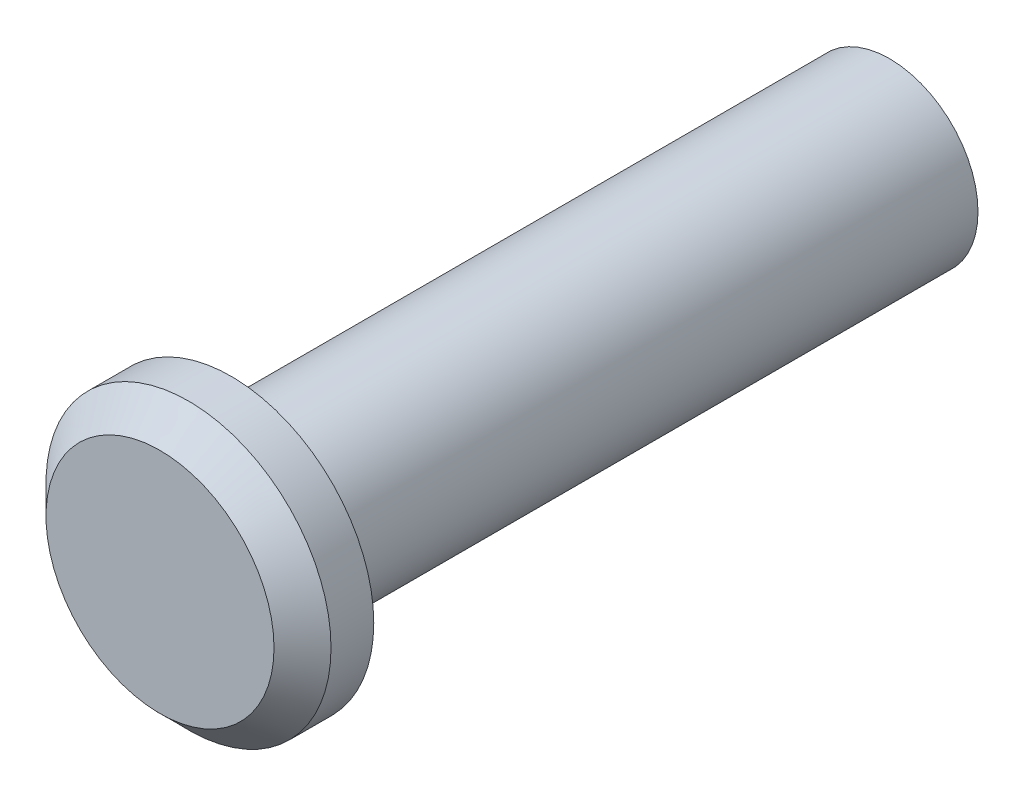
SolidWorks part; units mm, degrees
ref_plane "Front Plane" through (0, 0, 0) normal (0, 0, 1) x (1, 0, 0)
ref_plane "Top Plane" through (0, 0, 0) normal (0, 1, 0) x (1, 0, 0)
ref_plane "Right Plane" through (0, 0, 0) normal (1, 0, 0) x (0, 0, -1)
sketch "Sketch1" plane through (0, 0, 0) normal (0, 0, 1) x (1, 0, 0)
  circle A0 centre (0, 0) radius 7.874
  dimension "D1" = 15.748
extrude "Boss-Extrude1" add sketch "Sketch1" against normal blind 65.024
sketch "Sketch2" plane through (0, 0, 0) normal (0, 0, 1) x (1, 0, 0)
  circle A0 centre (0, 0) radius 12.7
  dimension "D1" = 25.4
extrude "Boss-Extrude2" add sketch "Sketch2" against normal blind 6.35
chamfer "Chamfer1" distance 2.54 angle 45 1 edges at (12.7, 0, 0)
